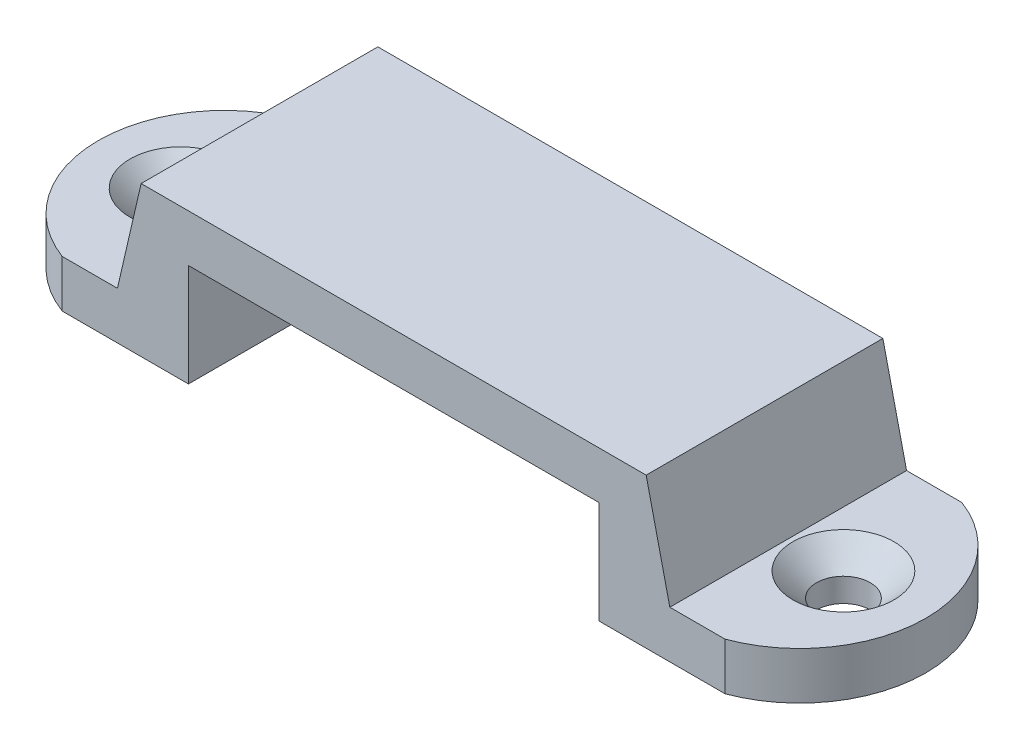
SolidWorks part; units mm, degrees
ref_plane "Front" through (0, 0, 0) normal (0, 0, 1) x (1, 0, 0)
ref_plane "Top" through (0, 0, 0) normal (0, 1, 0) x (1, 0, 0)
ref_plane "Right" through (0, 0, 0) normal (1, 0, 0) x (0, 0, -1)
sketch "Sketch2" plane through (0, 0, 0) normal (0, 0, 1) x (1, 0, 0)
  line L0 (1.5, 6.5) -> (0, 0)
  line L1 (-3.5, -3) -> (-3.5, 0)
  line L2 (-3.5, 0) -> (0, 0)
  line L4 (1.5, 6.5) -> (33.5, 6.5)
  line L6 (35, 0) -> (38.5, 0)
  line L7 (38.5, 0) -> (38.5, -3)
  line L8 (38.5, -3) -> (30.5, -3)
  line L9 (30.5, -3) -> (30.5, 3.5)
  line L10 (30.5, 3.5) -> (4.5, 3.5)
  line L11 (4.5, 3.5) -> (4.5, -3)
  line L12 (4.5, -3) -> (-3.5, -3)
  line L13 (33.5, 6.5) -> (35, 0)
  dimension "D1" = 6.5
  dimension "D2" = 26
  dimension "D3" = 3
  dimension "D4" = 8
  dimension "D5" = 3.5
  dimension "D6" = 3
  dimension "D7" = 3
extrude "Boss-Extrude1" add sketch "Sketch2" along normal blind 15
sketch "Sketch3" plane through (0, 0, 0) normal (0, 1, 0) x (1, 0, 0)
  line L2 (-3.5, 0) -> (-3.5, -15)
  line L3 (38.5, 0) -> (38.5, -15)
  arc A0 (-3.5, 0) -> (-3.5, -15) centre (-0.7161, -7.5) ccw
  arc A1 (38.5, 0) -> (38.5, -15) centre (35.7161, -7.5) cw
  dimension "D1" = 8
extrude "Boss-Extrude2" add sketch "Sketch3" against normal up to surface (3 mm away) up to face at (0.5, -3, 7.5)
sketch "Sketch4" plane through (0, 0, 0) normal (0, 1, 0) x (1, 0, 0)
  line L0 (0, -15) -> (0, 0) construction
  line L1 (35, -15) -> (35, 0) construction
  line L2 (-8.7161, -7.5) -> (43.7161, -7.5) construction
  arc A0 (-3.5, 0) -> (-3.5, -15) centre (-0.7161, -7.5) ccw construction
  arc A1 (38.5, -15) -> (38.5, 0) centre (35.7161, -7.5) ccw construction
  point P0 (-3.5, -7.5)
  point P1 (38.5, -7.5)
  dimension "D1" = 3.5
  dimension "D2" = 3.5
hole_wizard "CSK for M3 Countersunk Flat Head Screw1" positions "Sketch5" profile "Sketch6" countersink size "M3" standard "ISO"
sketch "Sketch5" plane through (0, 0, 0) normal (0, 1, 0) x (1, 0, 0)
  point P0 (-3.5, -7.5)
  point P3 (38.5, -7.5)
sketch "Sketch6" plane through (-3.5, 0, 7.5) normal (1, 0, 0) x (0, 0, 1)
  line L0 (0, 0) -> (0, 65.0215)
  line L1 (0, 65.0215) -> (1.7, 64)
  line L2 (1.7, 64) -> (1.7, 1.5)
  line L3 (1.7, 1.5) -> (3.2, 0)
  line L5 (3.2, 0) -> (0, 0)
  line L6 (-1.7, 1.5) -> (-3.2, 0) construction
  line L10 (0, 65.0215) -> (-1.7, 64) construction
  line L11 (0, -6.35) -> (0, 107.95) construction
  dimension "Hole Dia." = 3.4
  dimension "Hole Depth" = 64
  dimension "Near C'Sink Dia." = 6.4
  dimension "Near C'Sink Angle" = 90
  dimension "Drill Angle" = 118
